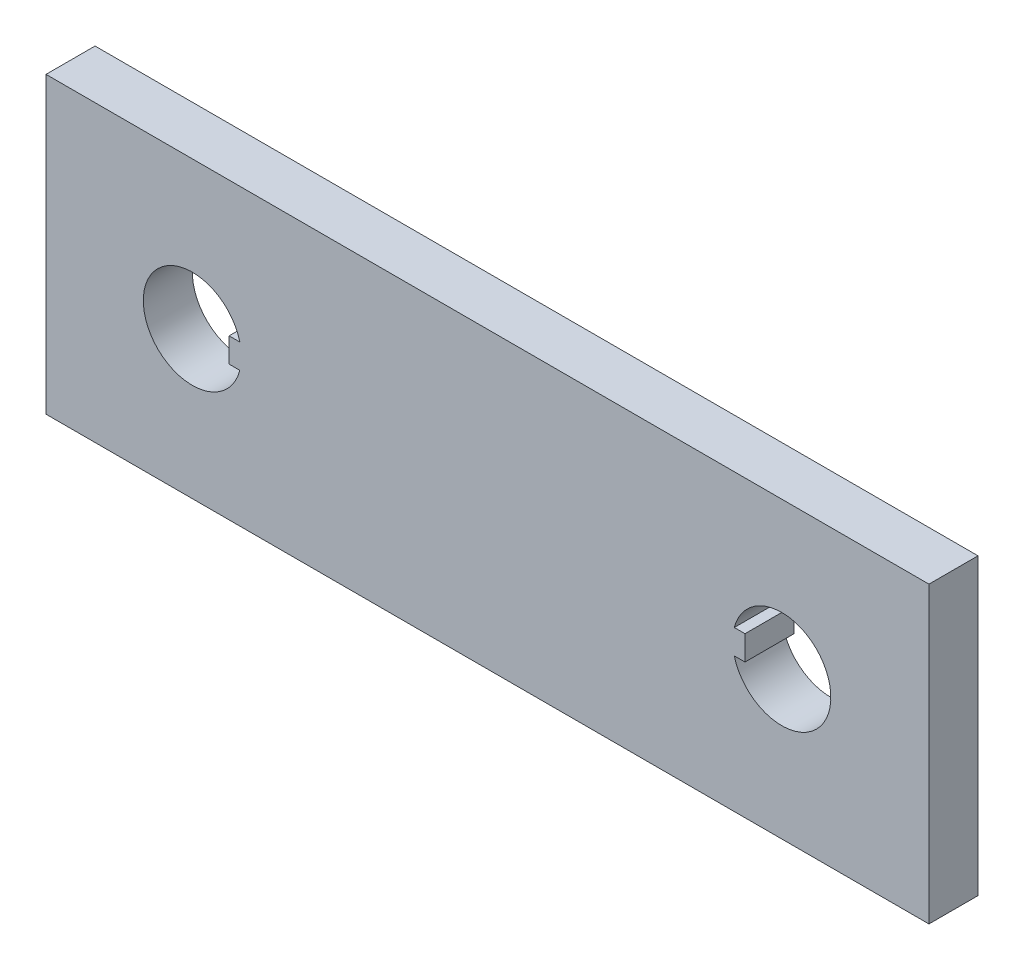
SolidWorks part; units mm, degrees
ref_plane "Front Plane" through (0, 0, 0) normal (0, 0, 1) x (1, 0, 0)
ref_plane "Top Plane" through (0, 0, 0) normal (0, 1, 0) x (1, 0, 0)
ref_plane "Right Plane" through (0, 0, 0) normal (1, 0, 0) x (0, 0, -1)
sketch "Sketch1" plane through (0, 0, 0) normal (0, 0, 1) x (1, 0, 0)
  line L1 (-57.15, -19.05) -> (57.15, -19.05)
  line L2 (-57.15, -19.05) -> (-57.15, 19.05)
  line L3 (-57.15, 19.05) -> (57.15, 19.05)
  line L4 (57.15, -19.05) -> (57.15, 19.05)
  line L5 (-57.15, -19.05) -> (57.15, 19.05) construction
  line L6 (-57.15, 19.05) -> (57.15, -19.05) construction
  point P0 (0, 0)
  dimension "D1" = 38.1
  dimension "D2" = 114.3
extrude "Boss-Extrude1" add sketch "Sketch1" along normal blind 6.35
sketch "Sketch2" plane through (0, 0, 6.35) normal (0, 0, 1) x (1, 0, 0)
  line L0 (0, 0) -> (-38.2053, 0) construction
  line L1 (0, 0) -> (38.1, 0) construction
  line B0 (31.952, -1.5887) -> (33.3375, -1.5887)
  line B1 (33.3375, -1.5887) -> (33.3375, 1.5863)
  line B2 (31.9513, 1.5863) -> (33.3375, 1.5863)
  arc B3 (31.952, -1.5887) -> (31.9513, 1.5863) centre (38.1, 0) ccw
  line B4 (-32.0573, 1.5887) -> (-33.4428, 1.5887)
  line B5 (-33.4428, 1.5887) -> (-33.4428, -1.5863)
  line B6 (-32.0566, -1.5863) -> (-33.4428, -1.5863)
  arc B7 (-32.0573, 1.5887) -> (-32.0566, -1.5863) centre (-38.2053, 0) ccw
  dimension "D1" = 38.2053
  dimension "D2" = 38.1
sketch_block_instance "Block-CutPattern-1"
sketch_block "Block-CutPattern" parameters "D1"=3.175, "D2"=1.5875
sketch_block_instance "Block-CutPattern-2"
extrude "Cut-Extrude1" cut sketch "Sketch2" against normal through all
